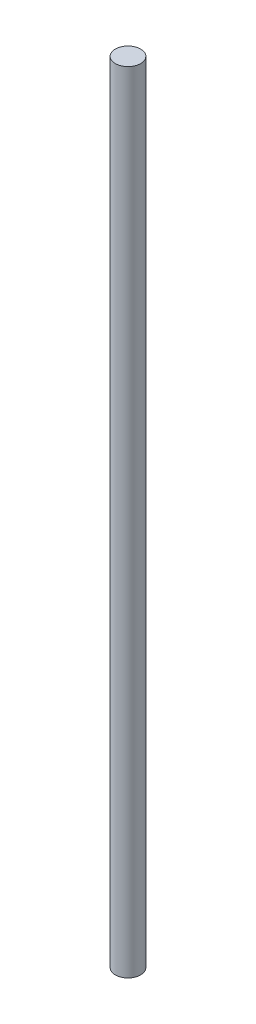
SolidWorks part; units mm, degrees
ref_plane "Front Plane" through (0, 0, 0) normal (0, 0, 1) x (1, 0, 0)
ref_plane "Top Plane" through (0, 0, 0) normal (0, 1, 0) x (1, 0, 0)
ref_plane "Right Plane" through (0, 0, 0) normal (1, 0, 0) x (0, 0, -1)
sketch "Sketch1" plane through (0, 0, 0) normal (0, 1, 0) x (1, 0, 0)
  circle A0 centre (0, 0) radius 0.4
  dimension "D1" = 0.8
extrude "Boss-Extrude1" add sketch "Sketch1" along normal blind 25
